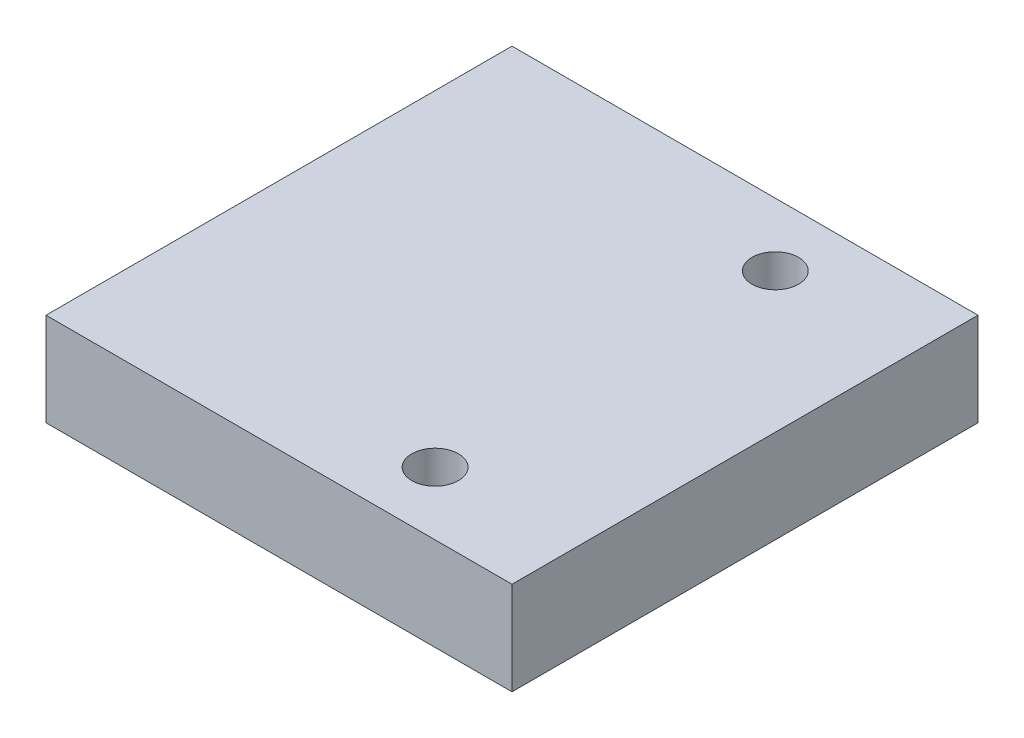
SolidWorks part; units mm, degrees
ref_plane "Plano frontal" through (0, 0, 0) normal (0, 0, 1) x (1, 0, 0)
ref_plane "Plano superior" through (0, 0, 0) normal (0, 1, 0) x (1, 0, 0)
ref_plane "Plano direito" through (0, 0, 0) normal (1, 0, 0) x (0, 0, -1)
sketch "Esboço2" plane through (0, 0, 0) normal (0, 1, 0) x (1, 0, 0)
  line L1 (-25, -25) -> (25, -25)
  line L2 (-25, -25) -> (-25, 25)
  line L3 (-25, 25) -> (25, 25)
  line L4 (25, -25) -> (25, 25)
  line L5 (-25, -25) -> (25, 25) construction
  line L6 (-25, 25) -> (25, -25) construction
  point P0 (0, 0)
  dimension "D1" = 50
  dimension "D2" = 50
extrude "Ressalto-extrusão2" add sketch "Esboço2" along normal blind 10
sketch "Esboço5" plane through (0, 10, 0) normal (0, 1, 0) x (1, 0, 0)
  line L0 (10, 27.5237) -> (10, -26.8195) construction
  line L1 (-30.6203, 0) -> (34.1735, 0) construction
  line L2 (25, -25) -> (25, 25) construction
  circle A0 centre (10, 18.25) radius 2.5
  circle A1 centre (10, -18.25) radius 2.5
  dimension "D1" = 5
  dimension "D2" = 5
  dimension "D3" = 18.25
  dimension "D4" = 18.25
  dimension "D5" = 15
extrude "Corte-extrusão5" cut sketch "Esboço5" against normal through all
